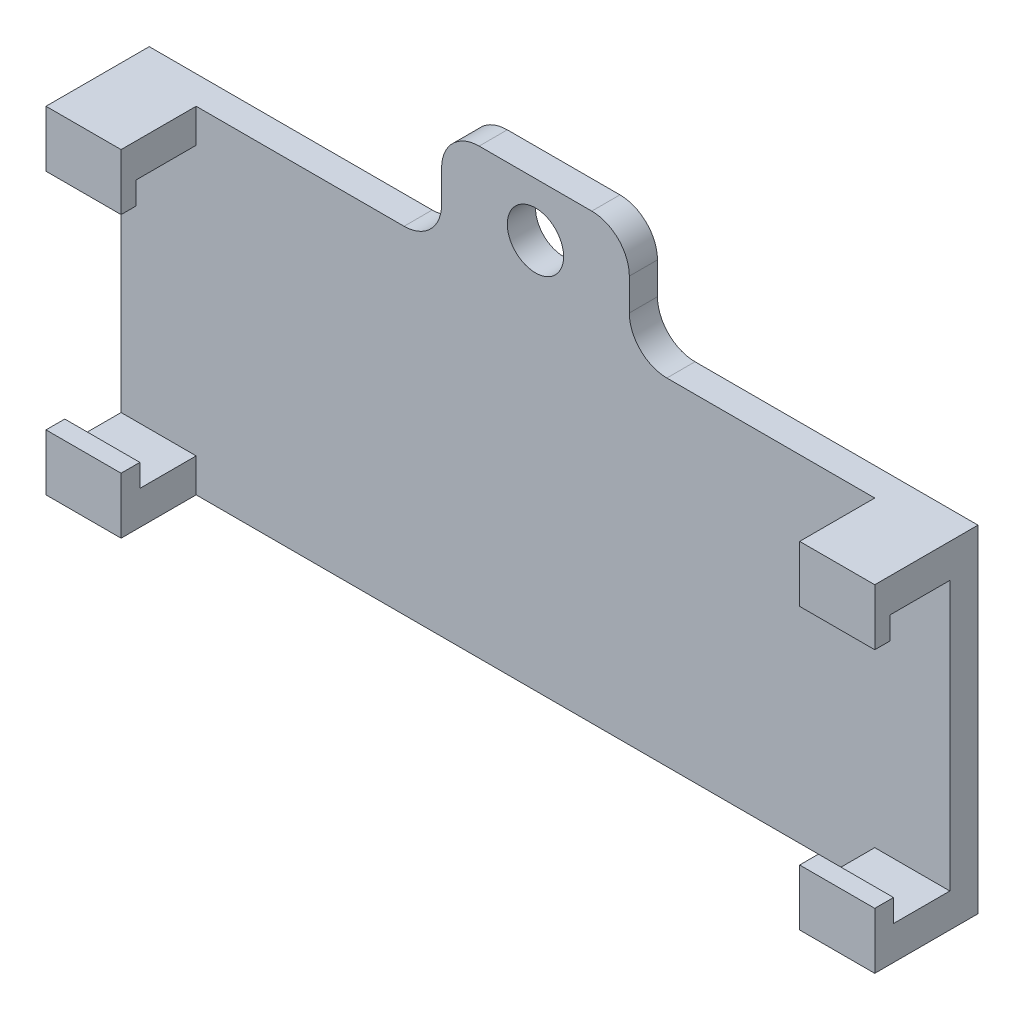
SolidWorks part; units mm, degrees
ref_plane "Front" through (0, 0, 0) normal (0, 0, 1) x (1, 0, 0)
ref_plane "Top" through (0, 0, 0) normal (0, 1, 0) x (1, 0, 0)
ref_plane "Right" through (0, 0, 0) normal (1, 0, 0) x (0, 0, -1)
sketch "Sketch1" plane through (0, 0, 0) normal (0, 1, 0) x (1, 0, 0)
  line L1 (0, 0) -> (44.15, 0)
  line L2 (0, 0) -> (0, 29.33)
  line L3 (0, 29.33) -> (44.15, 29.33)
  line L4 (44.15, 0) -> (44.15, 29.33)
  dimension "D1" = 44.15
  dimension "D2" = 29.33
extrude "Boss-Extrude1" add sketch "Sketch1" along normal blind 1.5
sketch "Sketch2" plane through (0, 1.5, 0) normal (0, 1, 0) x (1, 0, 0)
  line L0 (0, 29.33) -> (0, 0) construction
  line L1 (0, 20.63) -> (44.15, 20.63)
  line L2 (0, 20.63) -> (0, 23.63)
  line L3 (0, 23.63) -> (44.15, 23.63)
  line L4 (44.15, 20.63) -> (44.15, 23.63)
  line L5 (44.15, 0) -> (44.15, 29.33) construction
  line L7 (0, 8.7) -> (44.15, 8.7)
  line L8 (0, 8.7) -> (0, 5.7)
  line L9 (0, 5.7) -> (44.15, 5.7)
  line L10 (44.15, 8.7) -> (44.15, 5.7)
  line L11 (22.075, 8.7) -> (22.075, 20.63) construction
  point P14 (0, 14.665)
  point P15 (22.075, 14.665)
  dimension "D2" = 3
  dimension "D3" = 3
  dimension "D1" = 11.93
extrude "Boss-Extrude2" add sketch "Sketch2" along normal blind 4
sketch "Sketch3" plane through (0, 0, -20.63) normal (0, 0, 1) x (1, 0, 0)
  line L0 (44.15, 5.5) -> (44.15, 1.5) construction
  line L1 (0, 1.5) -> (44.15, 1.5)
  line L2 (0, 1.5) -> (0, 4.7)
  line L3 (0, 4.7) -> (44.15, 4.7)
  line L4 (44.15, 1.5) -> (44.15, 4.7)
  dimension "D1" = 3.2
extrude "Cut-Extrude1" cut sketch "Sketch3" against normal blind 1.2
sketch "Sketch4" plane through (0, 0, -8.7) normal (0, 0, -1) x (-1, 0, 0)
  line L0 (0, 5.5) -> (0, 1.5) construction
  line L1 (-44.15, 1.5) -> (0, 1.5)
  line L2 (-44.15, 1.5) -> (-44.15, 4.5)
  line L3 (-44.15, 4.5) -> (0, 4.5)
  line L4 (0, 1.5) -> (0, 4.5)
  dimension "D1" = 3
extrude "Cut-Extrude2" cut sketch "Sketch4" against normal blind 1.2
sketch "Sketch5" plane through (0, 1.5, 0) normal (0, 1, 0) x (1, 0, 0)
  line L0 (0, 29.33) -> (0, 23.63) construction
  line L1 (44.15, 29.33) -> (0, 29.33) construction
  line L2 (0, 5.7) -> (0, 0) construction
  circle A0 centre (22.075, 26.48) radius 1.5
  circle A1 centre (22.075, 2.85) radius 1.5
  point P6 (0, 26.48)
  point P9 (22.075, 29.33)
  point P12 (0, 2.85)
  dimension "D1" = 3
  dimension "D2" = 3
extrude "Cut-Extrude3" cut sketch "Sketch5" against normal through all
sketch "Sketch6" plane through (0, 0, 0) normal (0, -1, 0) x (1, 0, 0)
  line L0 (22.075, -26.48) -> (22.075, -5.7)
  line L1 (0, -5.7) -> (44.15, -5.7) construction
sketch "Sketch7" plane through (0, 0, 0) normal (0, 1, 0) x (1, 0, 0)
  line L1 (0, 5.7) -> (44.15, 5.7)
  line L2 (0, 5.7) -> (0, 0)
  line L3 (0, 0) -> (44.15, 0)
  line L4 (44.15, 5.7) -> (44.15, 0)
extrude "Cut-Extrude4" cut sketch "Sketch7" along normal through all
sketch "Sketch8" plane through (0, 0, -5.7) normal (0, 0, 1) x (1, 0, 0)
  line L0 (0, 5.5) -> (44.15, 5.5) construction
  line L1 (4, 5.5) -> (40.15, 5.5)
  line L2 (4, 5.5) -> (4, 1.5)
  line L3 (4, 1.5) -> (40.15, 1.5)
  line L4 (40.15, 5.5) -> (40.15, 1.5)
  line L5 (0, 1.5) -> (44.15, 1.5) construction
  line L6 (0, 1.5) -> (4, 1.5) construction
  line L16 (0, 5.5) -> (0, 0) construction
  point P8 (22.075, 5.5)
  point P9 (22.075, 5.5)
  dimension "D1" = 4
extrude "Cut-Extrude5" cut sketch "Sketch8" against normal through all
sketch "Sketch9" plane through (0, 1.5, 0) normal (0, 1, 0) x (1, 0, 0)
  line L0 (4, 23.63) -> (0, 23.63) construction
  line L1 (0, 29.33) -> (17.075, 29.33)
  line L2 (0, 29.33) -> (0, 23.63)
  line L3 (0, 23.63) -> (17.075, 23.63)
  line L4 (17.075, 29.33) -> (17.075, 23.63)
  line L5 (22.075, 29.33) -> (22.075, 5.7) construction
  line L6 (44.15, 29.33) -> (0, 29.33) construction
  line L7 (4, 5.7) -> (40.15, 5.7) construction
  line L8 (27.075, 29.33) -> (27.075, 23.63)
  line L9 (44.15, 23.63) -> (27.075, 23.63)
  line L10 (44.15, 29.33) -> (44.15, 23.63)
  line L11 (44.15, 29.33) -> (27.075, 29.33)
  dimension "D1" = 5
extrude "Cut-Extrude6" cut sketch "Sketch9" against normal through all
fillet "Fillet1" radius 2 4 edges at (17.075, 0.75, -23.63) (17.075, 0.75, -29.33) (27.075, 0.75, -29.33) (27.075, 0.75, -23.63)
move or copy body "Body-Move/Copy1" bodies to move or copy 109 copy no rotation origin (0, 2.75, -20.7) rotation axis (1, 0, 0) rotation angle 90
equation "\"Board Length\" = 14.33'The dimension of the board parallel with the clips"
equation "\"Board Width\"= 44.15'The dimension of the board perpendicular to the clips"
equation "\"D1@Sketch1\"=\"Board Width\""
equation "\"Board Slot Length\"= \"Board Length\" - 2 * \"Overhang Cut\""
equation "\"Overhang Cut\"= 1.2"
equation "\"D1@Cut-Extrude1\"=\"Overhang Cut\""
equation "\"D1@Sketch2\"=\"Board Slot Length\""
equation "\"Mount Length\"= \"Board Length\" + 7.5 * 2"
equation "\"D2@Sketch1\"=\"Mount Length\""
